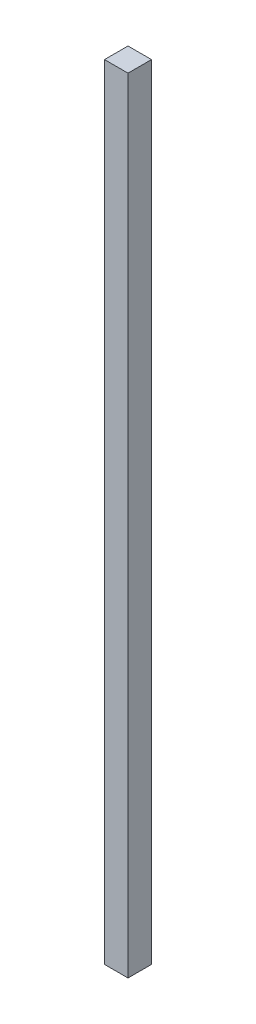
SolidWorks part; units mm, degrees
ref_plane "Front Plane" through (0, 0, 0) normal (0, 0, 1) x (1, 0, 0)
ref_plane "Top Plane" through (0, 0, 0) normal (0, 1, 0) x (1, 0, 0)
ref_plane "Right Plane" through (0, 0, 0) normal (1, 0, 0) x (0, 0, -1)
sketch "Sketch1" plane through (0, 0, 0) normal (0, 1, 0) x (1, 0, 0)
  line L1 (-15, -15) -> (15, -15)
  line L2 (-15, -15) -> (-15, 15)
  line L3 (-15, 15) -> (15, 15)
  line L4 (15, -15) -> (15, 15)
  line L5 (-15, -15) -> (15, 15) construction
  line L6 (-15, 15) -> (15, -15) construction
  point P0 (0, 0)
  dimension "D1" = 30
  dimension "D2" = 30
extrude "Boss-Extrude1" add sketch "Sketch1" along normal blind 1000
